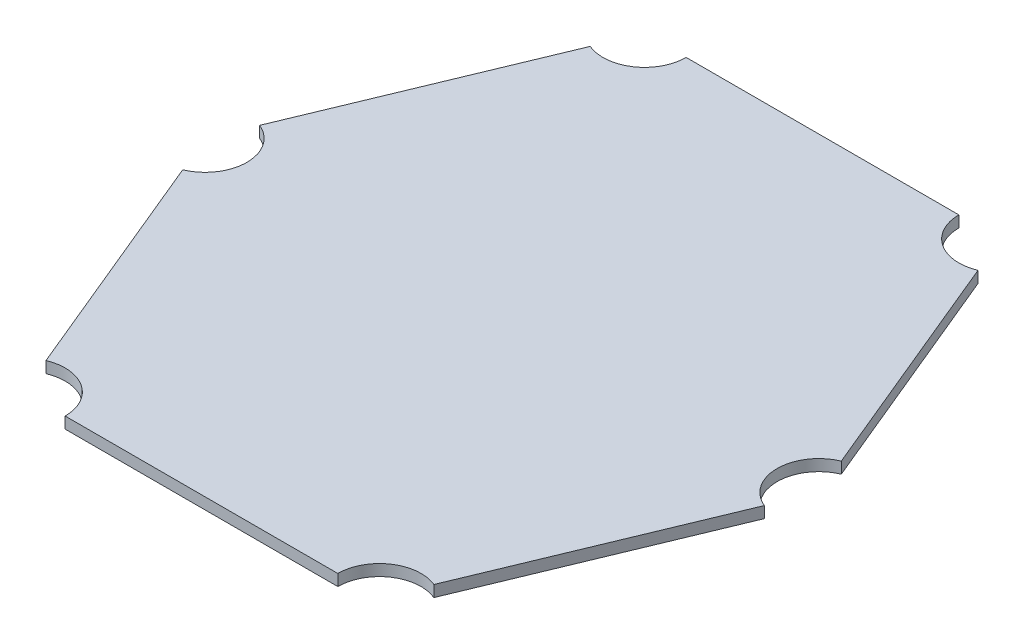
SolidWorks part; units mm, degrees
ref_plane "前视基准面" through (0, 0, 0) normal (0, 0, 1) x (1, 0, 0)
ref_plane "上视基准面" through (0, 0, 0) normal (0, 1, 0) x (1, 0, 0)
ref_plane "右视基准面" through (0, 0, 0) normal (1, 0, 0) x (0, 0, -1)
other "Configuration Table"
sketch "草图4" plane through (0, 0, 0) normal (0, 1, 0) x (1, 0, 0)
  line L0 (0, 0) -> (50.254, 0) construction
  line L1 (0, 0) -> (0, 95.6732) construction
  line L2 (-47, 82) -> (47, 82)
  line L3 (-47, 82) -> (-81, 0)
  line L4 (47, 82) -> (81, 0)
  line L5 (47, -82) -> (81, 0)
  line L6 (-47, -82) -> (47, -82)
  line L7 (-47, -82) -> (-81, 0)
  dimension "D1" = 94
  dimension "D2" = 94
  dimension "D3" = 82
  dimension "D4" = 162
extrude "凸台-拉伸1" add sketch "草图4" along normal blind 3
sketch "草图5" plane through (0, 3, 0) normal (0, 1, 0) x (1, 0, 0)
  circle A0 centre (-81, 0) radius 11
  circle A1 centre (81, 0) radius 11
  circle A2 centre (47, -82) radius 11
  circle A3 centre (-47, -82) radius 11
  circle A4 centre (-47, 82) radius 11
  circle A5 centre (47, 82) radius 11
  dimension "D1" = 22
extrude "切除-拉伸2" cut sketch "草图5" against normal through all
